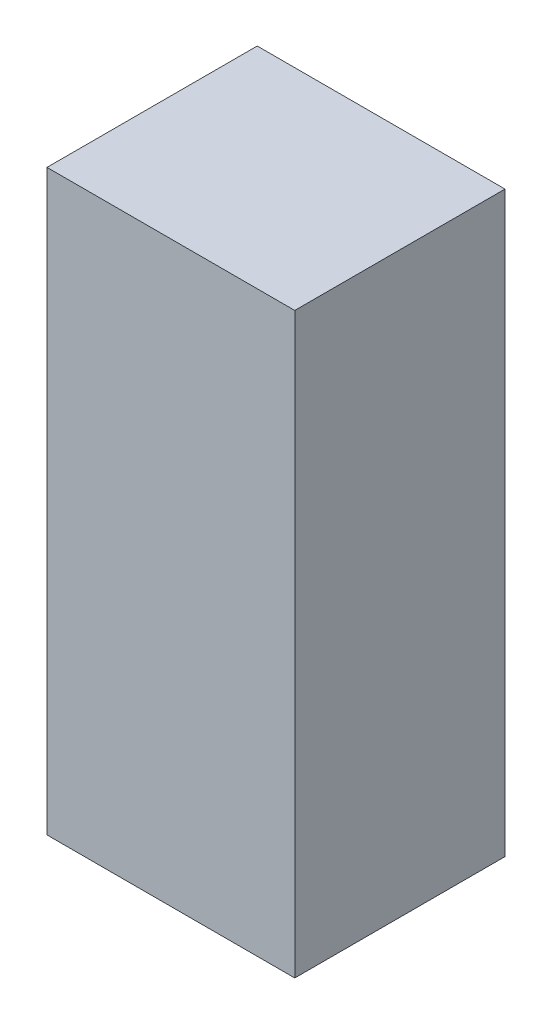
SolidWorks part; units mm, degrees
ref_plane "Front Plane" through (0, 0, 0) normal (1, 0, 0) x (0, 1, 0)
ref_plane "Top Plane" through (0, 0, 0) normal (0, 0, 1) x (0, 1, 0)
ref_plane "Right Plane" through (0, 0, 0) normal (0, 1, 0) x (-1, 0, 0)
sketch "Sketch1" plane through (0, 0, 0) normal (0, 0, 1) x (0, 1, 0)
  line L1 (0, 0) -> (77, 0)
  line L2 (0, 0) -> (0, 33)
  line L3 (0, 33) -> (77, 33)
  line L4 (77, 0) -> (77, 33)
  dimension "D1" = 77
  dimension "D2" = 33
extrude "Boss-Extrude1" add sketch "Sketch1" along normal blind 28
